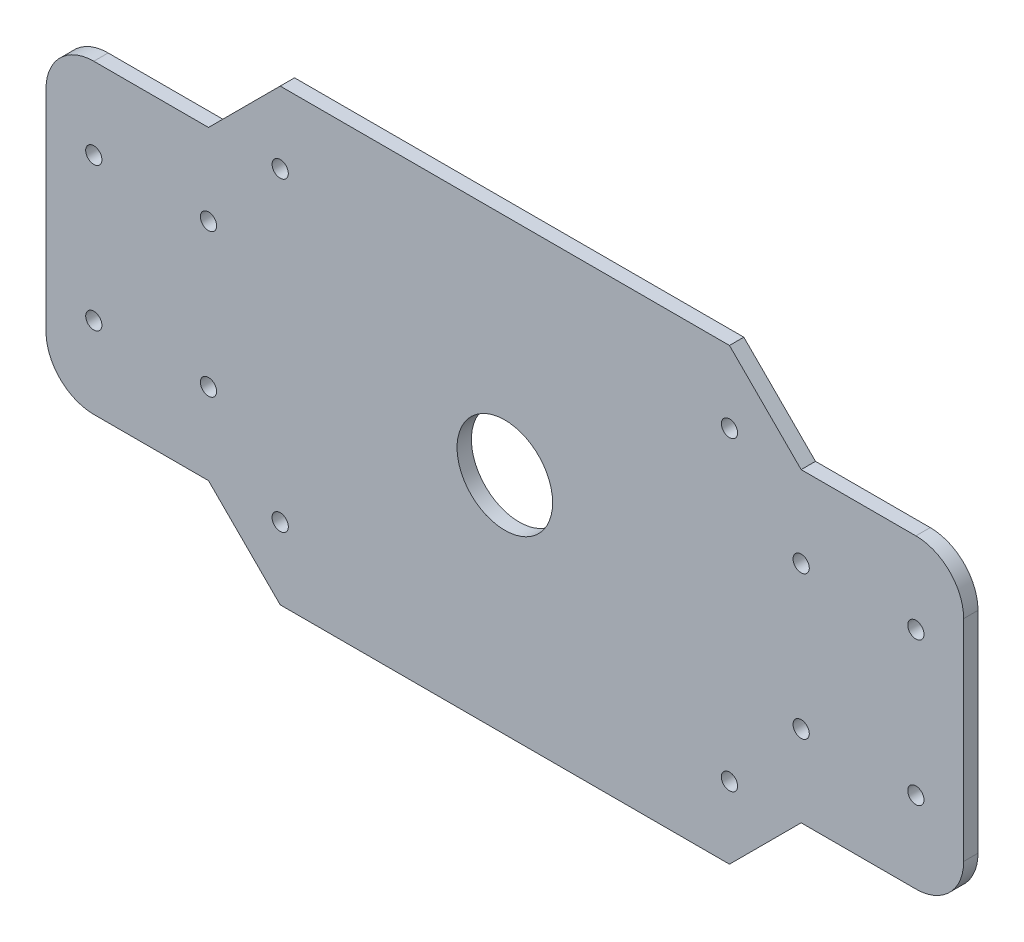
SolidWorks part; units mm, degrees
ref_plane "Front Plane" through (0, 0, 0) normal (0, 0, 1) x (1, 0, 0)
ref_plane "Top Plane" through (0, 0, 0) normal (0, 1, 0) x (1, 0, 0)
ref_plane "Right Plane" through (0, 0, 0) normal (1, 0, 0) x (0, 0, -1)
sketch "Sketch2" plane through (0, 0, 0) normal (0, 0, 1) x (1, 0, 0)
  line L0 (-62, -14.5498) -> (-47, 0.4502)
  line L5 (-86, -14.5498) -> (-62, -14.5498)
  line L7 (-86, -78.5498) -> (-62, -78.5498)
  line L9 (-47, 0.4502) -> (47, 0.4502)
  line L10 (47, 0.4502) -> (62, -14.5498)
  line L11 (-62, -78.5498) -> (-47, -93.5498)
  line L12 (-47, -93.5498) -> (47, -93.5498)
  line L13 (47, -93.5498) -> (62, -78.5498)
  line L14 (62, -14.5498) -> (86, -14.5498)
  line L15 (62, -78.5498) -> (86, -78.5498)
  line L18 (-96, -24.5498) -> (-96, -68.5498)
  line L19 (96, -24.5498) -> (96, -68.5498)
  line L20 (-86, -14.5498) -> (-86, -24.5498) construction
  line L21 (-86, -61.5498) -> (-86, -68.5498) construction
  line L22 (47, -78.5498) -> (47, -93.5498) construction
  line L23 (62, -31.5498) -> (86, -31.5498) construction
  line L24 (-86, -31.5498) -> (-62, -31.5498) construction
  line L25 (-62, -31.5498) -> (-62, -61.5498) construction
  line L26 (-62, -61.5498) -> (-86, -61.5498) construction
  line L27 (-86, -61.5498) -> (-86, -31.5498) construction
  line L28 (-47, -14.5498) -> (47, -14.5498) construction
  line L29 (47, -14.5498) -> (47, -78.5498) construction
  line L30 (47, -78.5498) -> (-47, -78.5498) construction
  line L31 (-47, -78.5498) -> (-47, -14.5498) construction
  line L32 (-62, -14.5498) -> (-47, -14.5498) construction
  line L33 (-47, -14.5498) -> (-47, 0.4502) construction
  line L34 (47, 0.4502) -> (47, -14.5498) construction
  line L35 (47, -14.5498) -> (62, -14.5498) construction
  line L36 (47, -78.5498) -> (62, -78.5498) construction
  line L37 (-62, -78.5498) -> (-47, -78.5498) construction
  line L38 (-47, -78.5498) -> (-47, -93.5498) construction
  line L39 (86, -31.5498) -> (86, -61.5498) construction
  line L40 (86, -61.5498) -> (62, -61.5498) construction
  line L41 (62, -61.5498) -> (62, -31.5498) construction
  line L42 (86, -14.5498) -> (86, -24.5498) construction
  line L43 (86, -68.5498) -> (86, -78.5498) construction
  line L44 (96, -24.5498) -> (86, -24.5498) construction
  line L45 (86, -24.5498) -> (86, -31.5498) construction
  line L46 (96, -68.5498) -> (86, -68.5498) construction
  line L47 (86, -61.5498) -> (86, -68.5498) construction
  line L48 (-96, -24.5498) -> (-86, -24.5498) construction
  line L49 (-86, -24.5498) -> (-86, -31.5498) construction
  line L50 (-96, -68.5498) -> (-86, -68.5498) construction
  line L51 (-86, -78.5498) -> (-86, -68.5498) construction
  line L52 (0, -46.5498) -> (0, 0.4502) construction
  line L53 (0, -46.5498) -> (0, -93.5498) construction
  line L54 (0, -46.5498) -> (-47, -46.5498) construction
  line L55 (0, -46.5498) -> (47, -46.5498) construction
  line L56 (-62, -31.5498) -> (-62, -14.5498) construction
  line L57 (-62, -61.5498) -> (-62, -78.5498) construction
  line L58 (62, -61.5498) -> (62, -78.5498) construction
  line L59 (62, -31.5498) -> (62, -14.5498) construction
  circle A4 centre (-62, -31.5498) radius 1.7
  circle A5 centre (-86, -31.5498) radius 1.7
  circle A6 centre (-86, -61.5498) radius 1.7
  circle A7 centre (-62, -61.5498) radius 1.7
  circle A8 centre (86, -61.5498) radius 1.7
  circle A9 centre (62, -61.5498) radius 1.7
  circle A10 centre (86, -31.5498) radius 1.7
  circle A11 centre (62, -31.5498) radius 1.7
  circle A12 centre (0, -46.5498) radius 10
  circle A13 centre (-47, -14.5498) radius 1.7
  circle A14 centre (-47, -78.5498) radius 1.7
  circle A15 centre (47, -78.5498) radius 1.7
  circle A16 centre (47, -14.5498) radius 1.7
  arc A19 (96, -24.5498) -> (86, -14.5498) centre (86, -24.5498) ccw
  arc A21 (86, -78.5498) -> (96, -68.5498) centre (86, -68.5498) ccw
  arc A22 (-86, -14.5498) -> (-96, -24.5498) centre (-86, -24.5498) ccw
  arc A24 (-96, -68.5498) -> (-86, -78.5498) centre (-86, -68.5498) ccw
  point P47 (0, -46.5498)
  dimension "D3" = 20
  dimension "D4" = 24
  dimension "D5" = 30
  dimension "D6" = 24
  dimension "D7" = 10
  dimension "D10" = 94
  dimension "D11" = 64
  dimension "D13" = 15
  dimension "D23" = 15
extrude "Boss-Extrude4" add sketch "Sketch2" along normal blind 3
